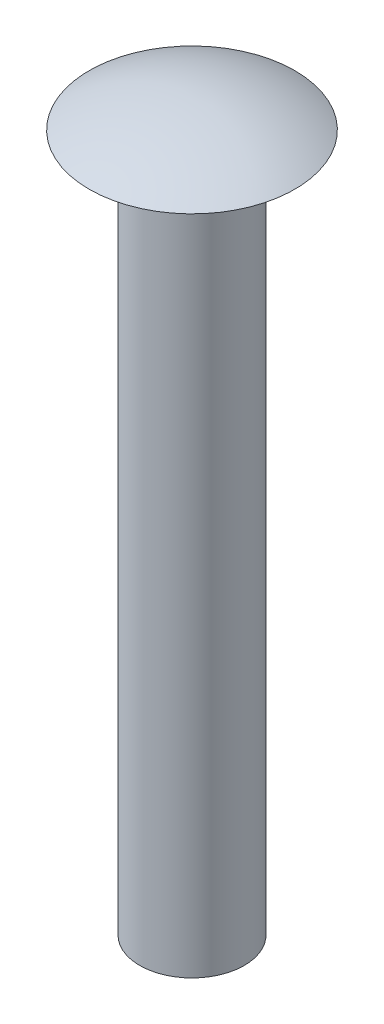
SolidWorks part; units mm, degrees
ref_plane "Front Plane" through (0, 0, 0) normal (0, 0, 1) x (1, 0, 0)
ref_plane "Top Plane" through (0, 0, 0) normal (0, 1, 0) x (1, 0, 0)
ref_plane "Right Plane" through (0, 0, 0) normal (1, 0, 0) x (0, 0, -1)
sketch "Sketch1" plane through (0, 0, 0) normal (1, 0, 0) x (0, 0, -1)
  line L0 (0, 7.1733) -> (0, -2.8267)
  line L1 (0, -2.8267) -> (-0.75, -2.8267)
  line L2 (-0.75, -2.8267) -> (-0.75, 7.5605)
  line L3 (0, 7.1733) -> (0.7243, 7.1733)
  arc A0 (0.7243, 7.1733) -> (-0.75, 7.5605) centre (-0.75, 4.5605) ccw
  dimension "D3" = 3
  dimension "D1" = 10
  dimension "D2" = 0.75
revolve "Revolve1" add sketch "Sketch1" angle 360 about L2
